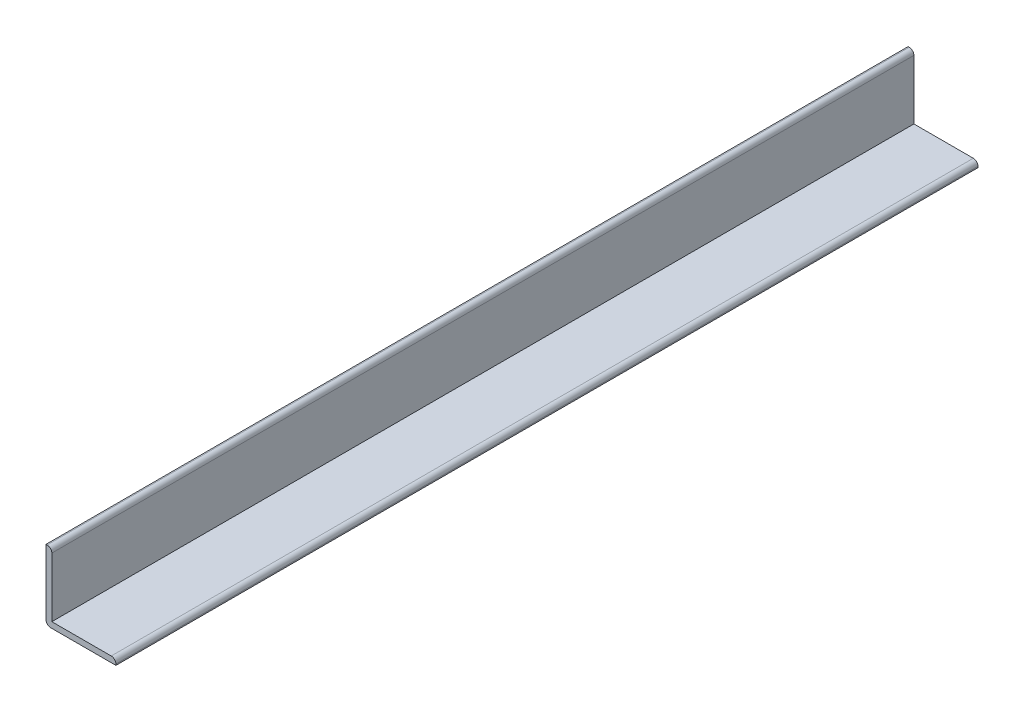
SolidWorks part; units mm, degrees
ref_plane "Front Plane" through (0, 0, 0) normal (0, 0, 1) x (1, 0, 0)
ref_plane "Top Plane" through (0, 0, 0) normal (0, 1, 0) x (1, 0, 0)
ref_plane "Right Plane" through (0, 0, 0) normal (1, 0, 0) x (0, 0, -1)
sketch "Sketch1" plane through (0, 0, 0) normal (0, 0, 1) x (1, 0, 0)
  line L0 (0, 2.54) -> (0, 38.1)
  line L1 (0, 38.1) -> (0.635, 38.1)
  line L2 (3.175, 35.56) -> (3.175, 3.175)
  line L3 (3.175, 3.175) -> (35.56, 3.175)
  line L4 (38.1, 0.635) -> (38.1, 0)
  line L5 (38.1, 0) -> (2.54, 0)
  arc A0 (2.54, 0) -> (0, 2.54) centre (2.54, 2.54) cw
  arc A1 (38.1, 0.635) -> (35.56, 3.175) centre (35.56, 0.635) ccw
  arc A2 (3.175, 35.56) -> (0.635, 38.1) centre (0.635, 35.56) ccw
  point P9 (0, 0)
  point P12 (38.1, 3.175)
  point P15 (3.175, 38.1)
  dimension "D4" = 2.54
  dimension "D1" = 38.1
  dimension "D2" = 3.175
  dimension "D3" = 38.1
  dimension "1/8" = 3.175
extrude "Boss-Extrude1" add sketch "Sketch1" along normal blind 469.9
